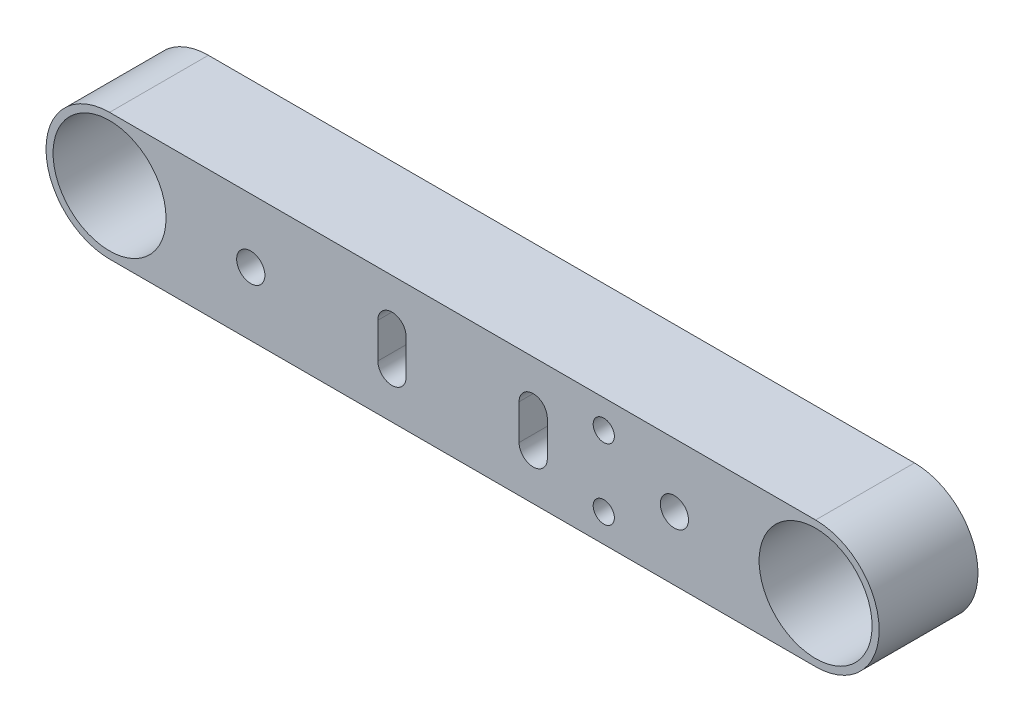
SolidWorks part; units mm, degrees
material "Nylon 101"
ref_plane "Front" through (0, 0, 0) normal (0, 0, 1) x (1, 0, 0)
ref_plane "Top" through (0, 0, 0) normal (0, 1, 0) x (1, 0, 0)
ref_plane "Right" through (0, 0, 0) normal (1, 0, 0) x (0, 0, -1)
sketch "Sketch1" plane through (0, 0, 0) normal (0, 0, 1) x (1, 0, 0)
  line L0 (50, 0) -> (-50, 0) construction
  line L3 (0, 0) -> (0, 5.4922) construction
  line L4 (-50, 0) -> (50, 0) construction
  line L5 (-50, 9) -> (50, 9)
  line L6 (-50, -9) -> (50, -9)
  line L7 (-10, -2.5) -> (-10, 2.5) construction
  line L8 (-10, 0) -> (10, 0) construction
  line L13 (-12, -2.5) -> (-12, 2.5)
  line L15 (-8, -2.5) -> (-8, 2.5)
  line L16 (10, -2.5) -> (10, 2.5) construction
  line L17 (12, -2.5) -> (12, 2.5)
  line L18 (8, -2.5) -> (8, 2.5)
  line L19 (20, -5) -> (20, 5) construction
  circle A2 centre (-30, 0) radius 2
  circle A3 centre (30, 0) radius 2
  circle A4 centre (-50, 0) radius 8
  circle A5 centre (50, 0) radius 8
  arc A6 (-50, 9) -> (-50, -9) centre (-50, 0) ccw
  arc A7 (50, -9) -> (50, 9) centre (50, 0) ccw
  arc A10 (-12, -2.5) -> (-8, -2.5) centre (-10, -2.5) ccw
  arc A11 (-8, 2.5) -> (-12, 2.5) centre (-10, 2.5) ccw
  arc A12 (12, -2.5) -> (8, -2.5) centre (10, -2.5) cw
  arc A13 (8, 2.5) -> (12, 2.5) centre (10, 2.5) cw
  circle A14 centre (20, -5) radius 1.5
  circle A15 centre (20, 5) radius 1.5
  point P4 (0, 0)
  point P5 (0, 0)
  point P20 (20, 5.4922)
  point P21 (0, 0)
  point P22 (10, -1.629)
  point P23 (0, 0)
  point P24 (10, 2.5)
  point P31 (-10, 0)
  point P40 (20, 0)
  point P43 (10, 0)
  dimension "D2" = 4
  dimension "D4" = 16
  dimension "D5" = 9
  dimension "D8" = 2
  dimension "D10" = 3
  dimension "D1" = 60
  dimension "D3" = 100
  dimension "D6" = 10
  dimension "D7" = 5
  dimension "D9" = 10
  dimension "D11" = 10
  dimension "D12" = 10
  dimension "D13" = 20
extrude "Boss-Extrude1" add sketch "Sketch1" along normal mid plane 14
